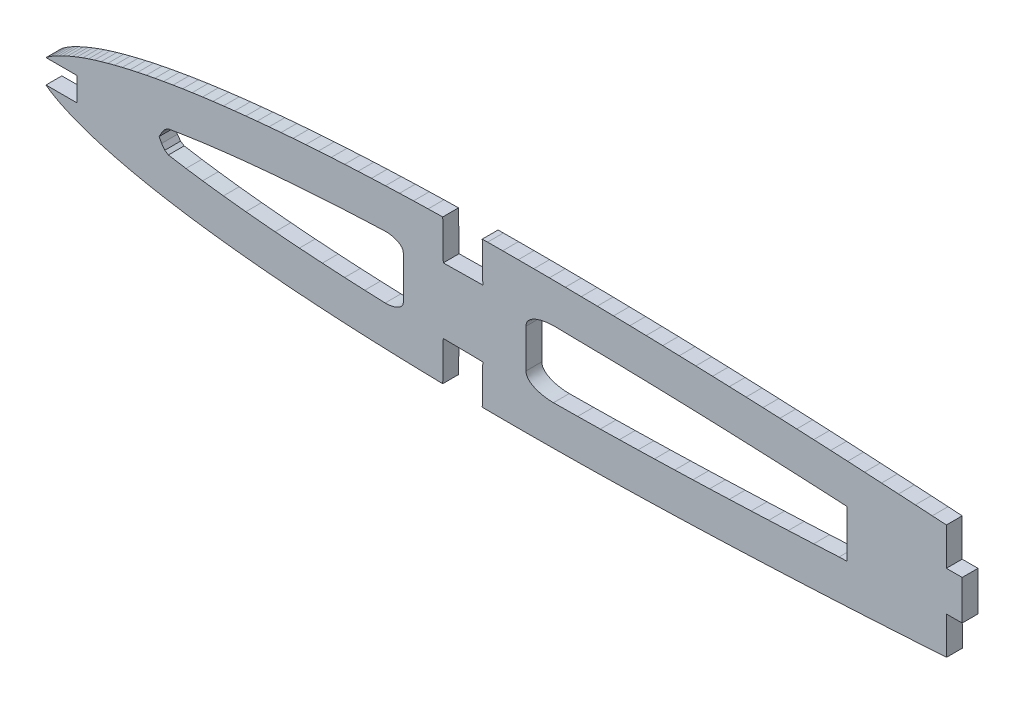
SolidWorks part; units mm, degrees
ref_plane "前视基准面" through (0, 0, 0) normal (0, 0, 1) x (1, 0, 0)
ref_plane "上视基准面" through (0, 0, 0) normal (0, 1, 0) x (1, 0, 0)
ref_plane "右视基准面" through (0, 0, 0) normal (1, 0, 0) x (0, 0, -1)
sketch "Model" plane through (0, 0, 0) normal (0, 0, 1) x (1, 0, 0)
  line L0 (163.6471, -193.6258) -> (167.57, -193.6258)
  line L1 (167.57, -193.6258) -> (167.57, -196.6258)
  line L2 (167.57, -196.6258) -> (163.6481, -196.6258)
  line L3 (218.8406, -185.9178) -> (218.91, -190.9168)
  line L4 (218.91, -190.9168) -> (213.91, -190.9858)
  line L5 (213.91, -190.9858) -> (213.841, -185.9868)
  line L6 (218.84, -204.3338) -> (218.909, -199.3338)
  line L7 (218.909, -199.3338) -> (213.909, -199.2648)
  line L8 (213.909, -199.2648) -> (213.841, -204.2648)
  line L9 (277.564, -187.8759) -> (275.777, -187.7638)
  line L10 (275.777, -187.7638) -> (273.64, -187.6348)
  line L11 (273.64, -187.6348) -> (271.502, -187.5078)
  line L12 (271.502, -187.5078) -> (269.357, -187.3828)
  line L13 (269.357, -187.3828) -> (267.212, -187.2598)
  line L14 (267.212, -187.2598) -> (265.067, -187.1408)
  line L15 (265.067, -187.1408) -> (262.922, -187.0268)
  line L16 (262.922, -187.0268) -> (260.778, -186.9188)
  line L17 (260.778, -186.9188) -> (258.632, -186.8148)
  line L18 (258.632, -186.8148) -> (256.495, -186.7168)
  line L19 (256.495, -186.7168) -> (254.358, -186.6228)
  line L20 (254.358, -186.6228) -> (252.22, -186.5338)
  line L21 (252.22, -186.5338) -> (250.1, -186.4508)
  line L22 (250.1, -186.4508) -> (247.981, -186.3718)
  line L23 (247.981, -186.3718) -> (245.861, -186.2988)
  line L24 (245.861, -186.2988) -> (243.766, -186.2318)
  line L25 (243.766, -186.2318) -> (241.671, -186.1698)
  line L26 (241.671, -186.1698) -> (239.576, -186.1138)
  line L27 (239.576, -186.1138) -> (237.515, -186.0648)
  line L28 (237.515, -186.0648) -> (235.455, -186.0208)
  line L29 (235.455, -186.0208) -> (233.393, -185.9828)
  line L30 (233.393, -185.9828) -> (231.374, -185.9518)
  line L31 (231.374, -185.9518) -> (229.355, -185.9288)
  line L32 (229.355, -185.9288) -> (227.336, -185.9108)
  line L33 (227.336, -185.9108) -> (225.366, -185.9008)
  line L34 (225.366, -185.9008) -> (223.396, -185.8978)
  line L35 (223.396, -185.8978) -> (221.426, -185.9008)
  line L36 (221.426, -185.9008) -> (219.513, -185.9108)
  line L37 (219.513, -185.9108) -> (218.8406, -185.9178)
  line L38 (213.841, -185.9868) -> (211.994, -186.0268)
  line L39 (211.994, -186.0268) -> (210.147, -186.0748)
  line L40 (210.147, -186.0748) -> (208.371, -186.1298)
  line L41 (208.371, -186.1298) -> (206.596, -186.1928)
  line L42 (206.596, -186.1928) -> (204.821, -186.2638)
  line L43 (204.821, -186.2638) -> (203.125, -186.3398)
  line L44 (203.125, -186.3398) -> (201.429, -186.4258)
  line L45 (201.429, -186.4258) -> (199.733, -186.5198)
  line L46 (199.733, -186.5198) -> (198.123, -186.6188)
  line L47 (198.123, -186.6188) -> (196.513, -186.7278)
  line L48 (196.513, -186.7278) -> (194.904, -186.8458)
  line L49 (194.904, -186.8458) -> (193.385, -186.9668)
  line L50 (193.385, -186.9668) -> (191.868, -187.0978)
  line L51 (191.868, -187.0978) -> (190.351, -187.2398)
  line L52 (190.351, -187.2398) -> (188.93, -187.3818)
  line L53 (188.93, -187.3818) -> (187.51, -187.5338)
  line L54 (187.51, -187.5338) -> (186.091, -187.6968)
  line L55 (186.091, -187.6968) -> (184.774, -187.8588)
  line L56 (184.774, -187.8588) -> (183.459, -188.0318)
  line L57 (183.459, -188.0318) -> (182.145, -188.2168)
  line L58 (182.145, -188.2168) -> (180.937, -188.3988)
  line L59 (180.937, -188.3988) -> (179.731, -188.5918)
  line L60 (179.731, -188.5918) -> (178.527, -188.7978)
  line L61 (178.527, -188.7978) -> (177.432, -188.9958)
  line L62 (177.432, -188.9958) -> (176.339, -189.2068)
  line L63 (176.339, -189.2068) -> (175.249, -189.4308)
  line L64 (175.249, -189.4308) -> (174.271, -189.6448)
  line L65 (174.271, -189.6448) -> (173.297, -189.8728)
  line L66 (173.297, -189.8728) -> (172.326, -190.1138)
  line L67 (172.326, -190.1138) -> (171.469, -190.3388)
  line L68 (171.469, -190.3388) -> (170.616, -190.5778)
  line L69 (170.616, -190.5778) -> (169.767, -190.8328)
  line L70 (169.767, -190.8328) -> (169.035, -191.0688)
  line L71 (169.035, -191.0688) -> (168.307, -191.3188)
  line L72 (168.307, -191.3188) -> (167.586, -191.5878)
  line L73 (167.586, -191.5878) -> (166.981, -191.8298)
  line L74 (166.981, -191.8298) -> (166.383, -192.0868)
  line L75 (166.383, -192.0868) -> (165.79, -192.3578)
  line L76 (165.79, -192.3578) -> (165.313, -192.5918)
  line L77 (165.313, -192.5918) -> (164.844, -192.8398)
  line L78 (164.844, -192.8398) -> (164.386, -193.1088)
  line L79 (164.386, -193.1088) -> (164.036, -193.3368)
  line L80 (164.036, -193.3368) -> (163.699, -193.5828)
  line L81 (163.699, -193.5828) -> (163.6471, -193.6258)
  line L82 (163.6481, -196.6258) -> (163.699, -196.6678)
  line L83 (163.699, -196.6678) -> (164.036, -196.9138)
  line L84 (164.036, -196.9138) -> (164.386, -197.1428)
  line L85 (164.386, -197.1428) -> (164.844, -197.4118)
  line L86 (164.844, -197.4118) -> (165.313, -197.6598)
  line L87 (165.313, -197.6598) -> (165.79, -197.8928)
  line L88 (165.79, -197.8928) -> (166.383, -198.1648)
  line L89 (166.383, -198.1648) -> (166.981, -198.4218)
  line L90 (166.981, -198.4218) -> (167.586, -198.6638)
  line L91 (167.586, -198.6638) -> (168.307, -198.9318)
  line L92 (168.307, -198.9318) -> (169.035, -199.1828)
  line L93 (169.035, -199.1828) -> (169.767, -199.4178)
  line L94 (169.767, -199.4178) -> (170.616, -199.6728)
  line L95 (170.616, -199.6728) -> (171.469, -199.9118)
  line L96 (171.469, -199.9118) -> (172.326, -200.1378)
  line L97 (172.326, -200.1378) -> (173.297, -200.3788)
  line L98 (173.297, -200.3788) -> (174.271, -200.6058)
  line L99 (174.271, -200.6058) -> (175.249, -200.8198)
  line L100 (175.249, -200.8198) -> (176.339, -201.0448)
  line L101 (176.339, -201.0448) -> (177.432, -201.2548)
  line L102 (177.432, -201.2548) -> (178.527, -201.4538)
  line L103 (178.527, -201.4538) -> (179.731, -201.6588)
  line L104 (179.731, -201.6588) -> (180.937, -201.8518)
  line L105 (180.937, -201.8518) -> (182.145, -202.0338)
  line L106 (182.145, -202.0338) -> (183.459, -202.2188)
  line L107 (183.459, -202.2188) -> (184.774, -202.3918)
  line L108 (184.774, -202.3918) -> (186.091, -202.5548)
  line L109 (186.091, -202.5548) -> (187.51, -202.7178)
  line L110 (187.51, -202.7178) -> (188.93, -202.8698)
  line L111 (188.93, -202.8698) -> (190.351, -203.0118)
  line L112 (190.351, -203.0118) -> (191.868, -203.1528)
  line L113 (191.868, -203.1528) -> (193.385, -203.2838)
  line L114 (193.385, -203.2838) -> (194.904, -203.4048)
  line L115 (194.904, -203.4048) -> (196.513, -203.5238)
  line L116 (196.513, -203.5238) -> (198.123, -203.6318)
  line L117 (198.123, -203.6318) -> (199.733, -203.7308)
  line L118 (199.733, -203.7308) -> (201.429, -203.8258)
  line L119 (201.429, -203.8258) -> (203.125, -203.9108)
  line L120 (203.125, -203.9108) -> (204.821, -203.9878)
  line L121 (204.821, -203.9878) -> (206.596, -204.0588)
  line L122 (206.596, -204.0588) -> (208.371, -204.1218)
  line L123 (208.371, -204.1218) -> (210.147, -204.1758)
  line L124 (210.147, -204.1758) -> (211.994, -204.2248)
  line L125 (211.994, -204.2248) -> (213.841, -204.2648)
  line L126 (218.84, -204.3338) -> (219.513, -204.3398)
  line L127 (219.513, -204.3398) -> (221.426, -204.3498)
  line L128 (221.426, -204.3498) -> (223.396, -204.3538)
  line L129 (223.396, -204.3538) -> (225.366, -204.3498)
  line L130 (225.366, -204.3498) -> (227.336, -204.3398)
  line L131 (227.336, -204.3398) -> (229.355, -204.3228)
  line L132 (229.355, -204.3228) -> (231.374, -204.2988)
  line L133 (231.374, -204.2988) -> (233.393, -204.2678)
  line L134 (233.393, -204.2678) -> (235.455, -204.2308)
  line L135 (235.455, -204.2308) -> (237.515, -204.1868)
  line L136 (237.515, -204.1868) -> (239.576, -204.1368)
  line L137 (239.576, -204.1368) -> (241.671, -204.0808)
  line L138 (241.671, -204.0808) -> (243.766, -204.0198)
  line L139 (243.766, -204.0198) -> (245.861, -203.9528)
  line L140 (245.861, -203.9528) -> (247.981, -203.8788)
  line L141 (247.981, -203.8788) -> (250.1, -203.8008)
  line L142 (250.1, -203.8008) -> (252.22, -203.7168)
  line L143 (252.22, -203.7168) -> (254.358, -203.6278)
  line L144 (254.358, -203.6278) -> (256.495, -203.5348)
  line L145 (256.495, -203.5348) -> (258.632, -203.4358)
  line L146 (258.632, -203.4358) -> (260.778, -203.3328)
  line L147 (260.778, -203.3328) -> (262.922, -203.2238)
  line L148 (262.922, -203.2238) -> (265.067, -203.1098)
  line L149 (265.067, -203.1098) -> (267.212, -202.9908)
  line L150 (267.212, -202.9908) -> (269.357, -202.8688)
  line L151 (269.357, -202.8688) -> (271.502, -202.7428)
  line L152 (271.502, -202.7428) -> (273.64, -202.6168)
  line L153 (273.64, -202.6168) -> (275.777, -202.4868)
  line L154 (275.777, -202.4868) -> (277.5808, -202.3746)
  line L155 (179.129, -193.6948) -> (181.3625, -193.3347)
  line L156 (181.3625, -193.3347) -> (183.459, -193.0318)
  line L157 (183.459, -193.0318) -> (186.091, -192.6968)
  line L158 (186.091, -192.6968) -> (188.93, -192.3818)
  line L159 (188.93, -192.3818) -> (192.6265, -192.0323)
  line L160 (192.6265, -192.0323) -> (195.7085, -191.7868)
  line L161 (195.7085, -191.7868) -> (198.6102, -191.5889)
  line L162 (198.6102, -191.5889) -> (201.429, -191.4258)
  line L163 (201.429, -191.4258) -> (203.973, -191.3018)
  line L164 (203.973, -191.3018) -> (206.596, -191.1928)
  line L165 (208.8498, -192.4088) -> (208.8498, -197.8429)
  line L166 (206.5564, -199.0572) -> (203.973, -198.9498)
  line L167 (203.973, -198.9498) -> (201.429, -198.8258)
  line L168 (201.429, -198.8258) -> (198.6102, -198.6628)
  line L169 (198.6102, -198.6628) -> (195.7085, -198.4648)
  line L170 (195.7085, -198.4648) -> (192.6265, -198.2193)
  line L171 (192.6265, -198.2193) -> (188.93, -197.8698)
  line L172 (188.93, -197.8698) -> (186.091, -197.5548)
  line L173 (186.091, -197.5548) -> (183.459, -197.2198)
  line L174 (183.459, -197.2198) -> (181.3625, -196.9169)
  line L175 (181.3625, -196.9169) -> (179.129, -196.5568)
  line L177 (227.8312, -190.897) -> (230.9123, -190.9466)
  line L178 (230.9123, -190.9466) -> (233.7796, -190.99)
  line L179 (233.7796, -190.99) -> (236.1935, -191.0366)
  line L180 (236.1935, -191.0366) -> (238.5455, -191.0893)
  line L181 (238.5455, -191.0893) -> (240.6235, -191.1418)
  line L182 (240.6235, -191.1418) -> (243.1916, -191.2148)
  line L183 (243.1916, -191.2148) -> (245.4948, -191.2871)
  line L184 (245.4948, -191.2871) -> (247.6115, -191.3591)
  line L185 (247.6115, -191.3591) -> (250.1, -191.4508)
  line L186 (250.1, -191.4508) -> (252.8662, -191.5607)
  line L187 (252.8662, -191.5607) -> (255.0843, -191.6548)
  line L188 (255.0843, -191.6548) -> (257.5635, -191.7658)
  line L189 (257.5635, -191.7658) -> (260.778, -191.9188)
  line L190 (260.778, -191.9188) -> (263.9945, -192.0838)
  line L191 (263.9945, -192.0838) -> (265.0108, -192.1432)
  line L192 (265.0108, -198.1394) -> (263.9945, -198.1678)
  line L193 (263.9945, -198.1678) -> (260.778, -198.3328)
  line L194 (260.778, -198.3328) -> (257.5635, -198.4858)
  line L195 (257.5635, -198.4858) -> (255.0843, -198.5969)
  line L196 (255.0843, -198.5969) -> (252.8662, -198.6909)
  line L197 (252.8662, -198.6909) -> (250.1, -198.8008)
  line L198 (250.1, -198.8008) -> (247.6115, -198.8926)
  line L199 (247.6115, -198.8926) -> (245.4948, -198.9645)
  line L200 (245.4948, -198.9645) -> (243.1916, -199.0368)
  line L201 (243.1916, -199.0368) -> (240.6235, -199.1098)
  line L202 (240.6235, -199.1098) -> (238.5455, -199.1623)
  line L203 (238.5455, -199.1623) -> (236.1935, -199.2151)
  line L204 (236.1935, -199.2151) -> (233.7796, -199.2617)
  line L205 (233.7796, -199.2617) -> (230.9123, -199.3051)
  line L206 (230.9123, -199.3051) -> (227.8511, -199.3362)
  line L207 (224.381, -197.5909) -> (224.381, -192.6826)
  line L208 (179.129, -193.6948) -> (178.6772, -193.9867)
  line L209 (178.6772, -193.9867) -> (178.2775, -194.5378)
  line L210 (178.2775, -194.5378) -> (177.9539, -195.1258)
  line L211 (179.129, -196.5568) -> (178.6772, -196.2649)
  line L212 (178.6772, -196.2649) -> (178.2775, -195.7139)
  line L213 (178.2775, -195.7139) -> (177.9539, -195.1258)
  line L214 (279.564, -195.1258) -> (279.564, -192.6258)
  line L215 (279.564, -195.1258) -> (279.564, -197.6258)
  line L216 (279.564, -192.6258) -> (277.564, -192.6258)
  line L217 (279.564, -197.6258) -> (277.564, -197.6258)
  line L218 (277.564, -192.6258) -> (277.564, -187.8759)
  line L219 (277.564, -197.6258) -> (277.5808, -202.3746)
  line L220 (265.0108, -192.1432) -> (265.0108, -198.1394)
  spline S0 degree 3 poles (206.596, -191.1928) (207.4489, -191.1574) (208.8498, -191.5551) (208.8498, -192.4088) knots 0 0 0 0 2.560885 2.560885 2.560885 2.560885
  spline S1 degree 3 poles (206.5564, -199.0572) (207.4206, -199.0931) (208.8498, -198.708) (208.8498, -197.8429) knots 0 0 0 0 2.595074 2.595074 2.595074 2.595074
  spline S2 degree 3 poles (224.381, -192.6826) (224.3659, -191.3877) (226.5363, -190.8989) (227.8312, -190.897) knots 0 0 0 0 3.884858 3.884858 3.884858 3.884858
  spline S3 degree 3 poles (224.381, -197.5909) (224.381, -198.8857) (226.5564, -199.3494) (227.8511, -199.3362) knots 0 0 0 0 3.884306 3.884306 3.884306 3.884306
  point P15 (213.841, -204.2678)
  point P19 (227.836, -190.9157)
  point P49 (0, 0)
  point P187 (227.8312, -190.897)
  point P203 (0, 0)
  point P227 (0, 0)
  point P229 (0, 0)
  point P231 (0, 0)
  point P232 (0, 0)
  point P233 (0, 0)
  point P234 (0, 0)
  point P235 (0, 0)
  point P236 (0, 0)
  point P237 (0, 0)
  point P238 (0, 0)
  point P239 (218.8401, -185.9227)
  point P240 (0, 0)
  point P241 (0, 0)
  point P242 (0, 0)
  point P243 (0, 0)
  point P244 (0, 0)
  point P245 (0, 0)
  point P246 (0, 0)
  point P247 (0, 0)
  point P248 (0, 0)
  point P249 (0, 0)
  point P250 (0, 0)
  point P251 (0, 0)
  point P252 (0, 0)
  point P253 (277.564, -197.6158)
  point P254 (213.841, -185.9828)
  point P255 (265.0291, -192.1618)
  point P256 (227.7857, -190.8647)
extrude "凸台-拉伸1" add sketch "Model" along normal blind 2
